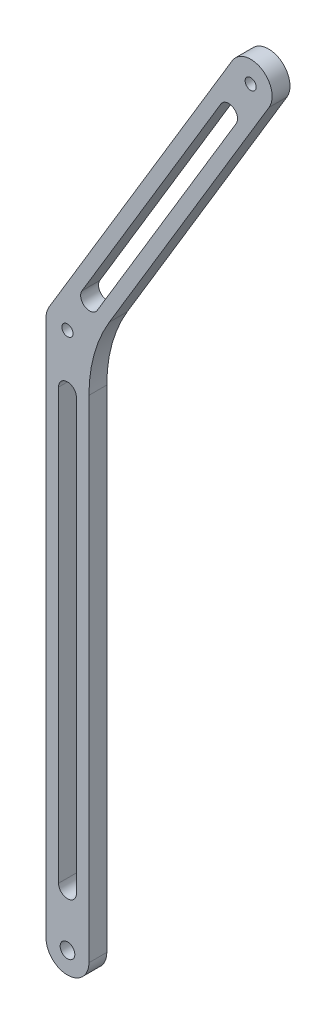
SolidWorks part; units mm, degrees
material "Hexcel AS4C (3000 丝)"
ref_plane "前视基准面" through (0, 0, 0) normal (0, 0, 1) x (1, 0, 0)
ref_plane "上视基准面" through (0, 0, 0) normal (0, 1, 0) x (1, 0, 0)
ref_plane "右视基准面" through (0, 0, 0) normal (1, 0, 0) x (0, 0, -1)
sketch "草图1" plane through (0, 0, 0) normal (0, 0, 1) x (1, 0, 0)
  line L0 (56.3885, 232.3985) -> (5.143, 147.1098)
  line L1 (46.1024, 238.5788) -> (-5.143, 153.2902)
  line L2 (-6, 150.2) -> (-6, 0)
  line L3 (6, 150.2) -> (6, 0)
  circle A0 centre (0, 0) radius 2.05
  circle A1 centre (51.2455, 235.4886) radius 1.55
  circle A2 centre (0, 150.2) radius 1.55
  circle A3 centre (0, 0) radius 6
  circle A4 centre (0, 150.2) radius 6
  circle A5 centre (51.2455, 235.4886) radius 6
  dimension "D1" = 3.1
  dimension "D2" = 150.2
  dimension "D3" = 99.5
  dimension "D4" = 241
  dimension "D5" = 12
  dimension "D6" = 4.1
extrude "凸台-拉伸1" add sketch "草图1" along normal blind 5 contours A4 L2 A3 L3 L0 | A3 A0 | A5 L1 A4 L3 L0 | A5 A1 | A4 A2 | A4 L0 L3
fillet "圆角1" radius 40 1 edges at (6, 148.5361, 2.5)
sketch "草图3" plane through (0, 0, 5) normal (0, 0, 1) x (1, 0, 0)
  line L0 (0, 148.65) -> (0, 0) construction
  line L1 (0, 135.2) -> (0, 15) construction
  line L2 (2.5, 135.2) -> (2.5, 15)
  line L3 (-2.5, 135.2) -> (-2.5, 15)
  circle A0 centre (0, 150.2) radius 1.55 construction
  arc A1 (2.5, 135.2) -> (-2.5, 135.2) centre (0, 135.2) ccw
  arc A2 (-2.5, 15) -> (2.5, 15) centre (0, 15) ccw
  point P7 (0, 75.1)
  dimension "D3" = 2.5
  dimension "D1" = 15
  dimension "D2" = 15
extrude "切除-拉伸1" cut sketch "草图3" against normal through all
sketch "草图4" plane through (0, 0, 5) normal (0, 0, 1) x (1, 0, 0)
  line L0 (0, 150.2) -> (51.2455, 235.4886) construction
  line L1 (45.0651, 225.2026) -> (6.1804, 160.4861) construction
  line L2 (47.208, 223.915) -> (8.3233, 159.1985)
  line L3 (42.9222, 226.4902) -> (4.0374, 161.7736)
  arc A0 (47.208, 223.915) -> (42.9222, 226.4902) centre (45.0651, 225.2026) ccw
  arc A1 (4.0374, 161.7736) -> (8.3233, 159.1985) centre (6.1804, 160.4861) ccw
  point P6 (25.6227, 192.8443)
  dimension "D3" = 2.5
  dimension "D1" = 12
  dimension "D2" = 12
extrude "切除-拉伸2" cut sketch "草图4" against normal through all
